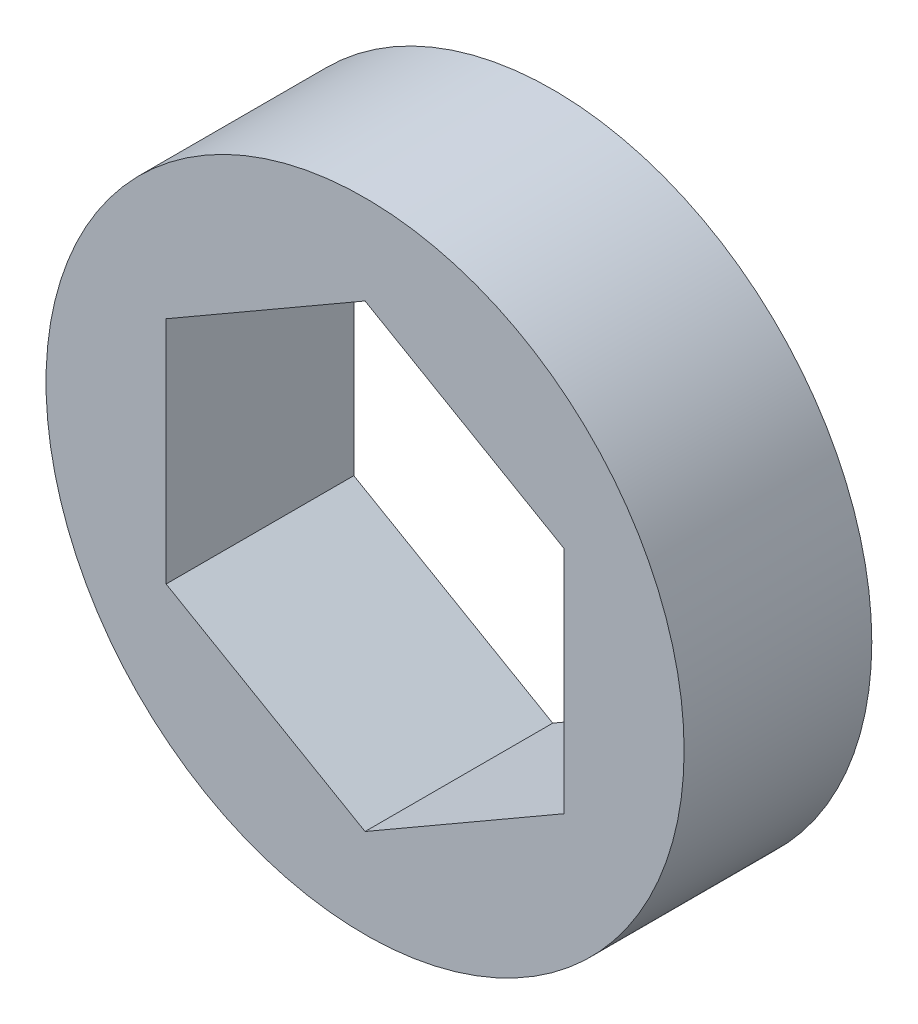
SolidWorks part; units mm, degrees
material "Nylon 101"
ref_plane "Front Plane" through (0, 0, 0) normal (0, 0, 1) x (1, 0, 0)
ref_plane "Top Plane" through (0, 0, 0) normal (0, 1, 0) x (1, 0, 0)
ref_plane "Right Plane" through (0, 0, 0) normal (1, 0, 0) x (0, 0, -1)
sketch "Sketch1" plane through (0, 0, 0) normal (0, 0, 1) x (1, 0, 0)
  line L1 (0, 7.7723) -> (-6.731, 3.8861)
  line L2 (-6.731, 3.8861) -> (-6.731, -3.8861)
  line L3 (-6.731, -3.8861) -> (0, -7.7723)
  line L4 (0, -7.7723) -> (6.731, -3.8861)
  line L5 (6.731, -3.8861) -> (6.731, 3.8861)
  line L6 (6.731, 3.8861) -> (0, 7.7723)
  circle A0 centre (0, 0) radius 6.731 construction
  circle A1 centre (0, 0) radius 10.795
  dimension "D1" = 13.462
  dimension "D2" = 21.59
extrude "Boss-Extrude1" add sketch "Sketch1" along normal blind 6.35
